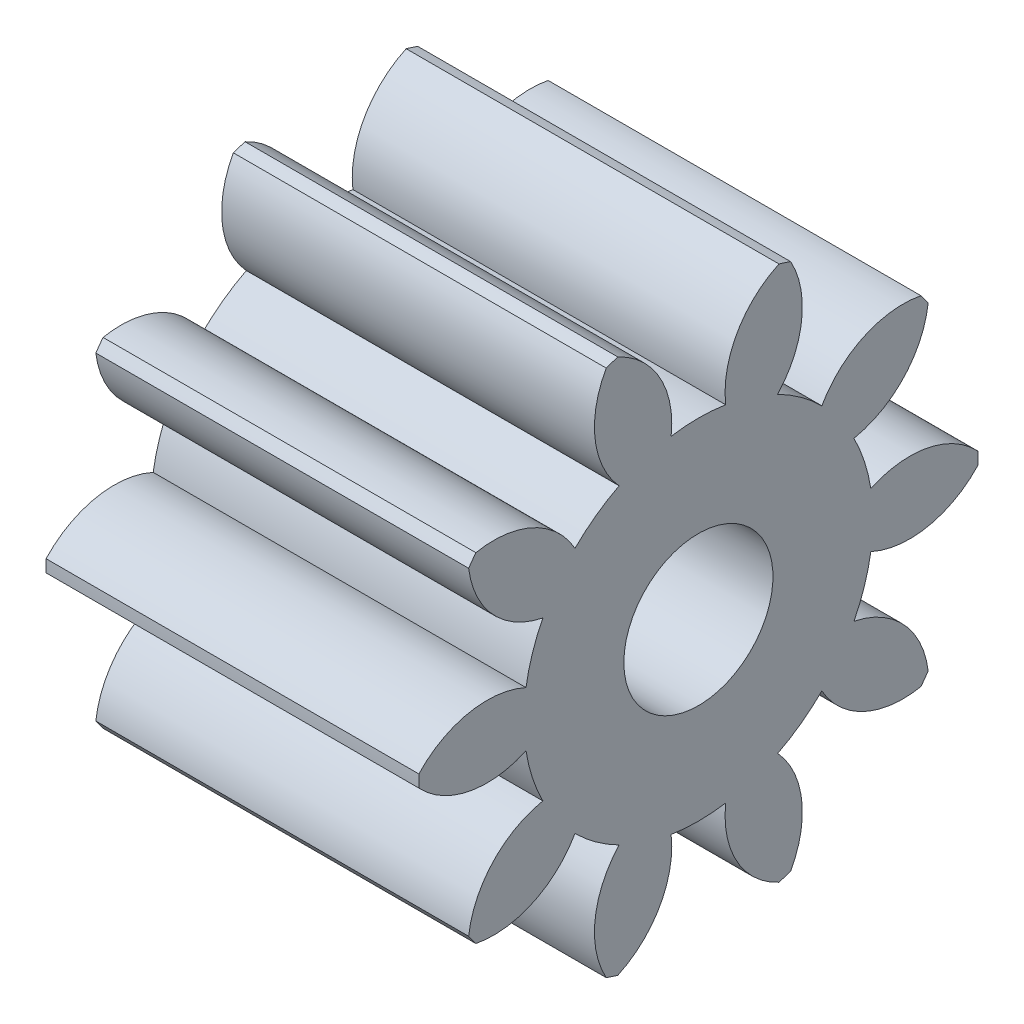
SolidWorks part; units mm, degrees
ref_plane "Plane1" through (0, 0, 0) normal (0, 0, 1) x (1, 0, 0)
ref_plane "Plane2" through (0, 0, 0) normal (0, 1, 0) x (1, 0, 0)
ref_plane "Plane3" through (0, 0, 0) normal (1, 0, 0) x (0, 0, -1)
sketch "HoldingSke" plane through (0, 0, 0) normal (0, 1, 0) x (1, 0, 0)
  line L0 (0, 0) -> (3.9392, -0.6946)
  line L1 (-15, 0) -> (100, 0) construction
  line L2 (0, 0) -> (-2.1039, 2.3779)
  line L3 (0, 0) -> (-11.863, 4.5341)
  line L4 (0, 0) -> (8.5048, 1.4996)
  line L5 (0, 0) -> (-46.8476, -17.4728)
  line L6 (0, 0) -> (-1.6579, -1.1186)
  line L7 (-2.1039, 2.3779) -> (8.6586, 51.2059)
  line L8 (-76.2, 54.61) -> (-76.1, 54.61)
  line L9 (-71.009, 38.7566) -> (-53.1078, 45.2721)
  line L10 (-76.2, 71.12) -> (104.1128, 71.12)
  line L11 (0, 0) -> (-2, 0)
  line L12 (-76.2, 101.6) -> (-76.192, 101.6)
  line L13 (24.9733, 27.94) -> (52.9518, 28.4284)
  line L14 (24.9733, 27.94) -> (24.9743, 27.94)
  line L15 (24.9733, 27.94) -> (100.4006, 29.5858)
  line L16 (-63.627, -0.25) -> (-12.827, -0.25)
  circle A0 centre (0, 0) radius 0.4
  circle A1 centre (0, 0) radius 0.9365
  circle A2 centre (0, 0) radius 37.5
  circle A3 centre (0, 0) radius 0.4
  dimension "MHD" = 1.873
  dimension "Hub_dia" = 75
  dimension "Bore" = 0.8
  dimension "MBD" = 0.8
  dimension "Num_teeth" = 10
  dimension "Pitch" = 4
  dimension "Overall_len" = 50
  dimension "Show_teeth" = 10
  dimension "Thickness" = 2
  dimension "OAL" = 50.0001
  dimension "T_dim" = 0.1
  dimension "Ap" = 20
  dimension "H" = 19.05
  dimension "Pitch_radius" = 180.3128
  dimension "Width" = 2
  dimension "Backlash" = 0.008
  dimension "Addendum_fac" = 1
  dimension "Dedendum_fac" = 1.25
  dimension "Clearance_fac" = 0.25
  dimension "Dedendum_add" = 0.001
  dimension "Module" = 0.25
sketch "BasProSke" plane through (0, 0, 0) normal (0, 1, 0) x (1, 0, 0)
  line L0 (-10, 0) -> (60, 0) construction
  line L1 (0, 0) -> (0, 1.5)
  line L2 (0, 0) -> (2, 0)
  line L3 (2, 0) -> (2, 1.5)
  line L4 (2, 1.5) -> (0, 1.5)
  dimension "Thickness" = 2
  dimension "Diameter" = 3
revolve "Base-Revolve" add sketch "BasProSke" angle 360 about L0
sketch "TooCutSke" plane through (0, 0, 0) normal (1, 0, 0) x (0, 0, -1)
  line L1 (0, 0) -> (0, 107) construction
  line L2 (0, 0) -> (-0.2095, 1.2323) construction
  line L3 (0, 0) -> (-0.7644, 2.3524) construction
  line L4 (-0.2095, 1.2323) -> (-0.3822, 1.1762) construction
  arc A0 (0.1463, 0.925) -> (-0.1463, 0.925) centre (0, 0) ccw
  arc A1 (0.4686, 1.4516) -> (-0.4686, 1.4516) centre (0, 0) ccw
  circle A2 centre (0, 0) radius 1.25 construction
  circle A3 centre (0, 0) radius 1.1746 construction
  arc A4 (-0.1463, 0.925) -> (-0.4686, 1.4516) centre (-0.6429, 0.983) ccw
  arc A5 (0.4686, 1.4516) -> (0.1463, 0.925) centre (0.6429, 0.983) ccw
  dimension "Root_dia" = 1.873
  dimension "Overcut_dia" = 3.0508
  dimension "Pitch_dia" = 2.5
  dimension "Base_dia" = 2.3492
  dimension "Flank_rad" = 0.5
  dimension "Half_ang" = 18
  dimension "Half_CT" = 0.1815
extrude "ToothCut" cut sketch "TooCutSke" along normal through all
fillet "Breaks" [suppressed] radius 0.005
fillet "RootFillets" [suppressed] radius 0.0635
pattern_circular "TeethCuts" count 10 every 36 about axis through (-10, 0, 0) along (1, 0, 0) of "ToothCut", "RootFillets", "Breaks"
sketch "HubNeaOneSke" plane through (0, 0, 0) normal (-1, 0, 0) x (0, 0, 1)
  circle A0 centre (0, 0) radius 0.9365
  dimension "Diameter" = 1.873
extrude "HubNearOne" [suppressed] add sketch "HubNeaOneSke" along normal blind 48.0001
sketch "HubNeaBotSke" plane through (0, 0, 0) normal (-1, 0, 0) x (0, 0, 1)
  circle A0 centre (0, 0) radius 0.9365
  dimension "Diameter" = 1.873
extrude "HubNearBoth" [suppressed] add sketch "HubNeaBotSke" along normal blind 24
ref_plane "FarPln" through (2, 0, 0) normal (1, 0, 0) x (0, 0, -1)
sketch "HubFarSke" plane through (2, 0, 0) normal (1, 0, 0) x (0, 0, -1)
  circle A0 centre (0, 0) radius 0.9365
  dimension "Diameter" = 1.873
extrude "HubFar" [suppressed] add sketch "HubFarSke" along normal blind 24
sketch "BorSke" plane through (0, 0, 0) normal (1, 0, 0) x (0, 0, -1)
  circle A0 centre (0, 0) radius 0.4
  dimension "Diameter" = 0.8
extrude "Bore" cut sketch "BorSke" along normal mid plane 100.0001
sketch "KeySke" plane through (0, 0, 0) normal (1, 0, 0) x (0, 0, -1)
  line L0 (-0.05, 0) -> (-0.05, 0.5)
  line L1 (-0.05, 0.5) -> (0.05, 0.5)
  line L2 (0.05, 0.5) -> (0.05, 0)
  line L3 (0, 0) -> (0, 34) construction
  line L4 (-0.05, 0) -> (0.05, 0)
  dimension "Offset" = 0.5
  dimension "Width" = 0.1
extrude "Keyway" [suppressed] cut sketch "KeySke" along normal mid plane 100.0001
pattern_circular "Keyway2" [suppressed] count 2 every 90 about axis through (-10, 0, 0) along (1, 0, 0)
equation "' \"Module@HoldingSke\" = 6.35"
equation "' \"Num_teeth@HoldingSke\" = 12"
equation "' \"Ap@HoldingSke\" =  20"
equation "' \"Ap@HoldingSke\" = 20"
equation "' \"Width@HoldingSke\" = 0.5 * 25.4"
equation "' \"Hub_dia@HoldingSke\"= 1 * 25.4"
equation "' \"Hub_dia@HoldingSke\" = 1 * 25.4"
equation "' \"Overall_len@HoldingSke\" = 1.0 * 25.4"
equation "' \"Bore@HoldingSke\" = 0.75 * 25.4"
equation "' \"T_dim@HoldingSke\" = 0.1 * 25.4"
equation "' \"Width@KeySke\" = 0.25 * 25.4"
equation "' \"Show_teeth@HoldingSke\" = 13"
equation "' \"Backlash@HoldingSke\" = 0.009 * 25.4"
equation "' \"Addendum_fac@HoldingSke\" = 1.0"
equation "' \"Dedendum_fac@HoldingSke\" = 1.25"
equation "' \"Dedendum_add@HoldingSke\" = 0.00005 * 25.4"
equation "' \"Clearance_fac@HoldingSke\" = 0.25"
equation "\"Pitch@HoldingSke\" = 1 / \"Module@HoldingSke\""
equation "\"Overcut_dia@TooCutSke\" = (\"Num_teeth@HoldingSke\" + 2 * \"Addendum_fac@HoldingSke\") / \"Pitch@HoldingSke\" + 0.002 * 25.4"
equation "\"Pitch_dia@TooCutSke\" = \"Num_teeth@HoldingSke\" / \"Pitch@HoldingSke\""
equation "\"Base_dia@TooCutSke\" = \"Num_teeth@HoldingSke\" / \"Pitch@HoldingSke\" * cos((\"Ap@HoldingSke\"  * 3.14159265 / 180))"
equation "\"Root_dia@TooCutSke\" = (\"Num_teeth@HoldingSke\" + 2) / \"Pitch@HoldingSke\" - 2 * (\"Addendum_fac@HoldingSke\" + \"Dedendum_fac@HoldingSke\") / \"Pitch@HoldingSke\" - \"Dedendum_add@HoldingSke\" * 2"
equation "\"Half_ang@TooCutSke\" = 180 / \"Num_teeth@HoldingSke\""
equation "\"Half_CT@TooCutSke\" = \"Num_teeth@HoldingSke\" / \"Pitch@HoldingSke\" * sin((3.14159265 / 2 / \"Num_teeth@HoldingSke\")) / 2 - 7 * \"Backlash@HoldingSke\" / 4"
equation "\"Flank_rad@TooCutSke\" = \"Num_teeth@HoldingSke\" / \"Pitch@HoldingSke\" / 5"
equation "\"Radius@RootFillets\" = \"Clearance_fac@HoldingSke\" / \"Pitch@HoldingSke\" + \"Dedendum_add@HoldingSke\""
equation "\"Break_rad@Breaks\" = 0.02 / \"Pitch@HoldingSke\""
equation "\"Thickness@HoldingSke\" = \"Width@HoldingSke\""
equation "\"OAL@HoldingSke\" = \"Thickness@HoldingSke\""
equation "\"MHD@HoldingSke\" = (\"Num_teeth@HoldingSke\" + 2) / \"Pitch@HoldingSke\" - 2 * (\"Addendum_fac@HoldingSke\" + \"Dedendum_fac@HoldingSke\")  / \"Pitch@HoldingSke\" - \"Dedendum_add@HoldingSke\" * 2"
equation "\"MBD@HoldingSke\" = (\"Num_teeth@HoldingSke\" + 2) / \"Pitch@HoldingSke\" - 2 * (\"Addendum_fac@HoldingSke\" + \"Dedendum_fac@HoldingSke\")  / \"Pitch@HoldingSke\" - \"Dedendum_add@HoldingSke\" * 2 - 0.002 * 25.4"
equation "\"MHD@HoldingSke\" = ((sgn( \"MHD@HoldingSke\" - \"Hub_dia@HoldingSke\" )-1)*( \"MHD@HoldingSke\" - \"Hub_dia@HoldingSke\" ))/-2+ \"Hub_dia@HoldingSke\""
equation "\"MBD@HoldingSke\" = ((sgn( \"MBD@HoldingSke\" - \"Bore@HoldingSke\" )-1)*( \"MBD@HoldingSke\" - \"Bore@HoldingSke\" ))/-2+ \"Bore@HoldingSke\""
equation "\"OAL@HoldingSke\" = ((sgn( \"OAL@HoldingSke\" - \"Overall_len@HoldingSke\" )+1)*( \"OAL@HoldingSke\" - \"Overall_len@HoldingSke\" ))/2 + \"Overall_len@HoldingSke\" + 0.000002 * 25.4"
equation "\"Num_teeth@TeethCuts\" = int( \"Show_teeth@HoldingSke\" ) + 1"
equation "\"Num_teeth@TeethCuts\" = ((sgn( \"Num_teeth@TeethCuts\" - \"Num_teeth@HoldingSke\" )-1)*( \"Num_teeth@TeethCuts\" - \"Num_teeth@HoldingSke\" ))/-2+ \"Num_teeth@HoldingSke\""
equation "\"Num_teeth@TeethCuts\" = ((sgn( \"Num_teeth@TeethCuts\" - 2.0)+1)*( \"Num_teeth@TeethCuts\" - 2.0))/2 +2.0"
equation "\"Angle@TeethCuts\" = 360.0 / \"Num_teeth@HoldingSke\""
equation "\"Diameter@BasProSke\" = (\"Num_teeth@HoldingSke\" + 2 * \"Addendum_fac@HoldingSke\") / \"Pitch@HoldingSke\""
equation "\"Thickness@BasProSke\"  = \"Thickness@HoldingSke\""
equation "' \"Fillet_rad@BasProSke\" =  \"Thickness@HoldingSke\" * 0.05"
equation "' \"Fillet_rad@BasProSke\" = \"Thickness@HoldingSke\" * 0.05"
equation "\"MHD@HoldingSke\" = ((sgn( \"MHD@HoldingSke\" - \"Root_dia@TooCutSke\" )-1)*( \"MHD@HoldingSke\" - \"Root_dia@TooCutSke\" ))/-2+ \"Root_dia@TooCutSke\""
equation "\"Diameter@HubNeaOneSke\" = \"MHD@HoldingSke\""
equation "\"Length@HubNearOne\" = \"OAL@HoldingSke\" - \"Thickness@BasProSke\""
equation "\"Diameter@HubNeaBotSke\" = \"MHD@HoldingSke\""
equation "\"Length@HubNearBoth\" = ( \"OAL@HoldingSke\" - \"Thickness@BasProSke\" ) / 2.0"
equation "\"Thickness@FarPln\" = \"Thickness@BasProSke\""
equation "\"Diameter@HubFarSke\" = \"MHD@HoldingSke\""
equation "\"Length@HubFar\" = ( \"OAL@HoldingSke\" - \"Thickness@BasProSke\" ) / 2.0"
equation "\"Diameter@BorSke\" = \"MBD@HoldingSke\""
equation "\"D1@Bore\" = \"OAL@HoldingSke\" * 2.0"
equation "\"D1@Keyway\" = \"OAL@HoldingSke\" * 2.0"
equation "\"Offset@KeySke\" = \"T_dim@HoldingSke\" + \"MBD@HoldingSke\" / 2.0"
